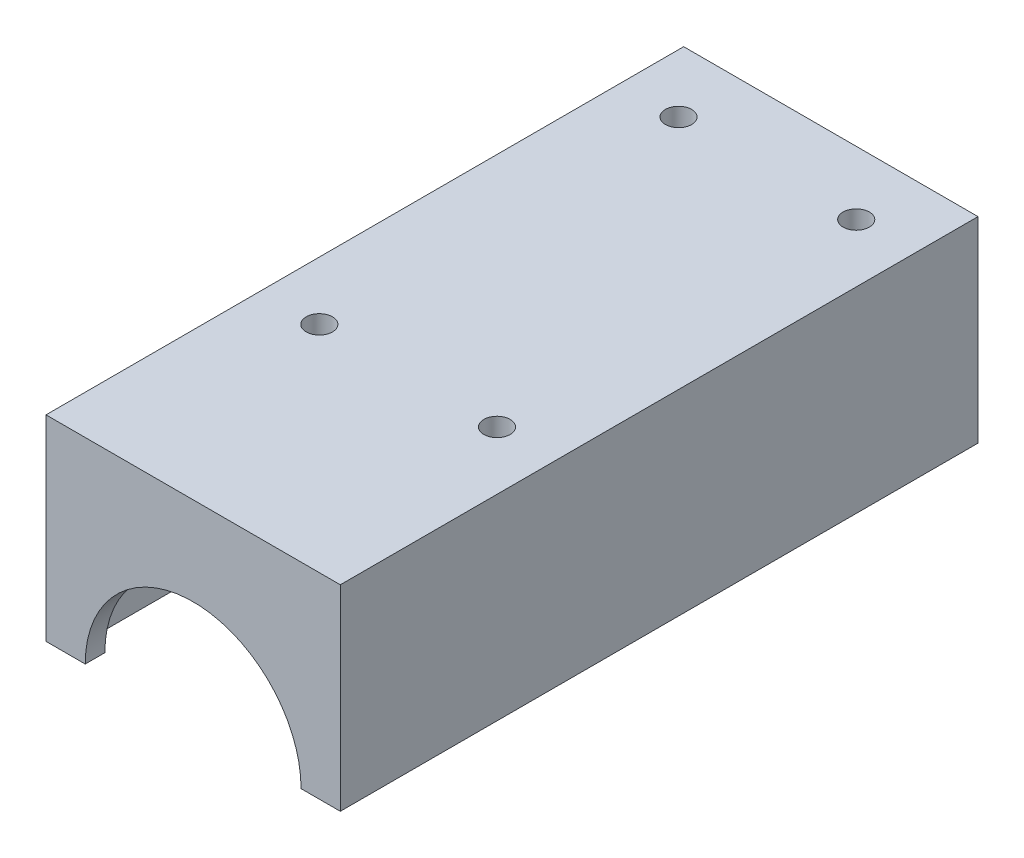
SolidWorks part; units mm, degrees
ref_plane "Front Plane" through (0, 0, 0) normal (0, 0, 1) x (1, 0, 0)
ref_plane "Top Plane" through (0, 0, 0) normal (0, 1, 0) x (1, 0, 0)
ref_plane "Right Plane" through (0, 0, 0) normal (1, 0, 0) x (0, 0, -1)
sketch "Sketch1" plane through (0, 0, 0) normal (0, 1, 0) x (1, 0, 0)
  line L1 (-19.05, -41.275) -> (19.05, -41.275)
  line L2 (-19.05, -41.275) -> (-19.05, 41.275)
  line L3 (-19.05, 41.275) -> (19.05, 41.275)
  line L4 (19.05, -41.275) -> (19.05, 41.275)
  line L5 (-19.05, -41.275) -> (19.05, 41.275) construction
  line L6 (-19.05, 41.275) -> (19.05, -41.275) construction
  point P0 (0, 0)
  dimension "D1" = 38.1
  dimension "D2" = 82.55
extrude "Boss-Extrude1" add sketch "Sketch1" along normal mid plane 25.4
shell "Shell1" thickness 2.54
sketch "Sketch2" plane through (0, 0, -41.275) normal (0, 0, -1) x (-1, 0, 0)
  line L0 (-19.05, -12.7) -> (19.05, -12.7) construction
  circle A3 centre (0, -12.7) radius 16.51 construction
  circle A4 centre (0, -12.7) radius 16.51 construction
  circle A5 centre (0, -12.7) radius 13.97
  dimension "D1" = 2.54
extrude "Cut-Extrude1" cut sketch "Sketch2" against normal through all
sketch "Sketch3" plane through (0, 10.16, 0) normal (0, -1, 0) x (1, 0, 0)
  circle A0 centre (11.5, 13.44) radius 1.7 construction
  circle A1 centre (11.5, -33.06) radius 1.7 construction
  circle A2 centre (-11.5, -33.06) radius 1.7 construction
  circle A3 centre (-11.5, 13.44) radius 1.7 construction
  circle A4 centre (11.5, 13.44) radius 1.7
  circle A5 centre (11.5, -33.06) radius 1.7
  circle A6 centre (-11.5, -33.06) radius 1.7
  circle A7 centre (-11.5, 13.44) radius 1.7
extrude "Cut-Extrude2" cut sketch "Sketch3" against normal through all
sketch "Sketch4" plane through (0, 10.16, 0) normal (0, -1, 0) x (1, 0, 0)
  circle A0 centre (11.5, 13.44) radius 1.7 construction
  circle A1 centre (-11.5, 13.44) radius 1.7 construction
  circle A2 centre (-11.5, -33.06) radius 1.7 construction
  circle A3 centre (11.5, -33.06) radius 1.7 construction
  circle A4 centre (11.5, 13.44) radius 1.7
  circle A5 centre (-11.5, 13.44) radius 1.7
  circle A6 centre (-11.5, -33.06) radius 1.7
  circle A7 centre (11.5, -33.06) radius 1.7
extrude "Extrude-Thin1" add sketch "Sketch4" along normal up to surface (11.43 mm away) thin
sketch "Sketch5" plane through (0, -1.27, 0) normal (0, -1, 0) x (1, 0, 0)
  line L0 (-12.7, 15.94) -> (12.7, 15.94) construction
  line L1 (-10.16, -15.94) -> (-9.525, -15.94)
  line L2 (-10.16, -15.94) -> (-10.16, 15.94)
  line L3 (-10.16, 15.94) -> (10.16, 15.94)
  line L4 (10.16, -15.94) -> (10.16, 15.94)
  line L5 (-10.16, -15.94) -> (10.16, 15.94) construction
  line L6 (-10.16, 15.94) -> (10.16, -15.94) construction
  line L7 (12.7, -35.56) -> (-12.7, -35.56) construction
  line L9 (9.525, -15.94) -> (9.525, -36.83)
  line L10 (9.525, -36.83) -> (-9.525, -36.83)
  line L11 (-9.525, -15.94) -> (-9.525, -36.83)
  line L12 (9.525, -15.94) -> (-9.525, -36.83) construction
  line L13 (9.525, -36.83) -> (-9.525, -15.94) construction
  line L14 (9.525, -15.94) -> (10.16, -15.94)
  point P0 (0, 0)
  point P8 (0, -26.385)
  point P15 (0, 0)
  dimension "D1" = 20.32
  dimension "D2" = 1.27
  dimension "D3" = 19.05
extrude "Cut-Extrude3" cut sketch "Sketch5" against normal blind 2.54
